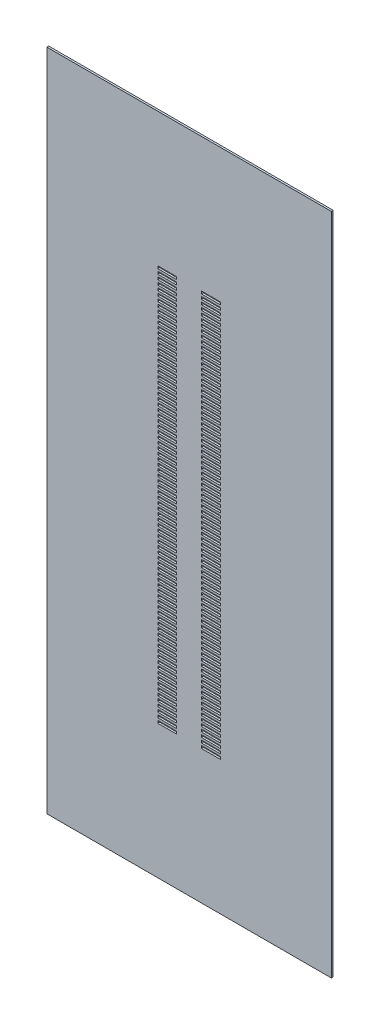
SolidWorks part; units mm, degrees
ref_plane "Front Plane" through (0, 0, 0) normal (0, 0, 1) x (1, 0, 0)
ref_plane "Top Plane" through (0, 0, 0) normal (0, 1, 0) x (1, 0, 0)
ref_plane "Right Plane" through (0, 0, 0) normal (1, 0, 0) x (0, 0, -1)
sketch "Sketch1" plane through (0, 0, 0) normal (0, 0, 1) x (1, 0, 0)
  line L1340 (-1.3, -0.27) -> (-1.3, 0)
  line L1341 (-1.3, 0) -> (-3.3, 0)
  line L1342 (-3.3, 0) -> (-3.3, -0.27)
  line L1343 (-3.3, -0.27) -> (-1.3, -0.27)
  line L2016 (-1.3, 0) -> (1.3, 0) construction
  line L2017 (0, 0) -> (0, -41.77) construction
  line L2018 (1.3, -0.27) -> (1.3, 0)
  line L2019 (3.3, -0.27) -> (1.3, -0.27)
  line L2020 (3.3, 0) -> (3.3, -0.27)
  line L2021 (1.3, 0) -> (3.3, 0)
  line L2022 (1.3, -0.5) -> (3.3, -0.5)
  line L2023 (3.3, -0.5) -> (3.3, -0.77)
  line L2024 (3.3, -0.77) -> (1.3, -0.77)
  line L2025 (1.3, -0.77) -> (1.3, -0.5)
  line L2026 (-1.3, -0.5) -> (-3.3, -0.5)
  line L2027 (-3.3, -0.5) -> (-3.3, -0.77)
  line L2028 (-3.3, -0.77) -> (-1.3, -0.77)
  line L2029 (-1.3, -0.77) -> (-1.3, -0.5)
  line L2030 (1.3, -1) -> (3.3, -1)
  line L2031 (3.3, -1) -> (3.3, -1.27)
  line L2032 (3.3, -1.27) -> (1.3, -1.27)
  line L2033 (1.3, -1.27) -> (1.3, -1)
  line L2034 (-1.3, -1) -> (-3.3, -1)
  line L2035 (-3.3, -1) -> (-3.3, -1.27)
  line L2036 (-3.3, -1.27) -> (-1.3, -1.27)
  line L2037 (-1.3, -1.27) -> (-1.3, -1)
  line L2038 (1.3, -1.5) -> (3.3, -1.5)
  line L2039 (3.3, -1.5) -> (3.3, -1.77)
  line L2040 (3.3, -1.77) -> (1.3, -1.77)
  line L2041 (1.3, -1.77) -> (1.3, -1.5)
  line L2042 (-1.3, -1.5) -> (-3.3, -1.5)
  line L2043 (-3.3, -1.5) -> (-3.3, -1.77)
  line L2044 (-3.3, -1.77) -> (-1.3, -1.77)
  line L2045 (-1.3, -1.77) -> (-1.3, -1.5)
  line L2046 (1.3, -2) -> (3.3, -2)
  line L2047 (3.3, -2) -> (3.3, -2.27)
  line L2048 (3.3, -2.27) -> (1.3, -2.27)
  line L2049 (1.3, -2.27) -> (1.3, -2)
  line L2050 (-1.3, -2) -> (-3.3, -2)
  line L2051 (-3.3, -2) -> (-3.3, -2.27)
  line L2052 (-3.3, -2.27) -> (-1.3, -2.27)
  line L2053 (-1.3, -2.27) -> (-1.3, -2)
  line L2054 (1.3, -2.5) -> (3.3, -2.5)
  line L2055 (3.3, -2.5) -> (3.3, -2.77)
  line L2056 (3.3, -2.77) -> (1.3, -2.77)
  line L2057 (1.3, -2.77) -> (1.3, -2.5)
  line L2058 (-1.3, -2.5) -> (-3.3, -2.5)
  line L2059 (-3.3, -2.5) -> (-3.3, -2.77)
  line L2060 (-3.3, -2.77) -> (-1.3, -2.77)
  line L2061 (-1.3, -2.77) -> (-1.3, -2.5)
  line L2062 (1.3, -3) -> (3.3, -3)
  line L2063 (3.3, -3) -> (3.3, -3.27)
  line L2064 (3.3, -3.27) -> (1.3, -3.27)
  line L2065 (1.3, -3.27) -> (1.3, -3)
  line L2066 (-1.3, -3) -> (-3.3, -3)
  line L2067 (-3.3, -3) -> (-3.3, -3.27)
  line L2068 (-3.3, -3.27) -> (-1.3, -3.27)
  line L2069 (-1.3, -3.27) -> (-1.3, -3)
  line L2070 (1.3, -3.5) -> (3.3, -3.5)
  line L2071 (3.3, -3.5) -> (3.3, -3.77)
  line L2072 (3.3, -3.77) -> (1.3, -3.77)
  line L2073 (1.3, -3.77) -> (1.3, -3.5)
  line L2074 (-1.3, -3.5) -> (-3.3, -3.5)
  line L2075 (-3.3, -3.5) -> (-3.3, -3.77)
  line L2076 (-3.3, -3.77) -> (-1.3, -3.77)
  line L2077 (-1.3, -3.77) -> (-1.3, -3.5)
  line L2078 (1.3, -4) -> (3.3, -4)
  line L2079 (3.3, -4) -> (3.3, -4.27)
  line L2080 (3.3, -4.27) -> (1.3, -4.27)
  line L2081 (1.3, -4.27) -> (1.3, -4)
  line L2082 (-1.3, -4) -> (-3.3, -4)
  line L2083 (-3.3, -4) -> (-3.3, -4.27)
  line L2084 (-3.3, -4.27) -> (-1.3, -4.27)
  line L2085 (-1.3, -4.27) -> (-1.3, -4)
  line L2086 (1.3, -4.5) -> (3.3, -4.5)
  line L2087 (3.3, -4.5) -> (3.3, -4.77)
  line L2088 (3.3, -4.77) -> (1.3, -4.77)
  line L2089 (1.3, -4.77) -> (1.3, -4.5)
  line L2090 (-1.3, -4.5) -> (-3.3, -4.5)
  line L2091 (-3.3, -4.5) -> (-3.3, -4.77)
  line L2092 (-3.3, -4.77) -> (-1.3, -4.77)
  line L2093 (-1.3, -4.77) -> (-1.3, -4.5)
  line L2094 (1.3, -5) -> (3.3, -5)
  line L2095 (3.3, -5) -> (3.3, -5.27)
  line L2096 (3.3, -5.27) -> (1.3, -5.27)
  line L2097 (1.3, -5.27) -> (1.3, -5)
  line L2098 (-1.3, -5) -> (-3.3, -5)
  line L2099 (-3.3, -5) -> (-3.3, -5.27)
  line L2100 (-3.3, -5.27) -> (-1.3, -5.27)
  line L2101 (-1.3, -5.27) -> (-1.3, -5)
  line L2102 (1.3, -5.5) -> (3.3, -5.5)
  line L2103 (3.3, -5.5) -> (3.3, -5.77)
  line L2104 (3.3, -5.77) -> (1.3, -5.77)
  line L2105 (1.3, -5.77) -> (1.3, -5.5)
  line L2106 (-1.3, -5.5) -> (-3.3, -5.5)
  line L2107 (-3.3, -5.5) -> (-3.3, -5.77)
  line L2108 (-3.3, -5.77) -> (-1.3, -5.77)
  line L2109 (-1.3, -5.77) -> (-1.3, -5.5)
  line L2110 (1.3, -6) -> (3.3, -6)
  line L2111 (3.3, -6) -> (3.3, -6.27)
  line L2112 (3.3, -6.27) -> (1.3, -6.27)
  line L2113 (1.3, -6.27) -> (1.3, -6)
  line L2114 (-1.3, -6) -> (-3.3, -6)
  line L2115 (-3.3, -6) -> (-3.3, -6.27)
  line L2116 (-3.3, -6.27) -> (-1.3, -6.27)
  line L2117 (-1.3, -6.27) -> (-1.3, -6)
  line L2118 (1.3, -6.5) -> (3.3, -6.5)
  line L2119 (3.3, -6.5) -> (3.3, -6.77)
  line L2120 (3.3, -6.77) -> (1.3, -6.77)
  line L2121 (1.3, -6.77) -> (1.3, -6.5)
  line L2122 (-1.3, -6.5) -> (-3.3, -6.5)
  line L2123 (-3.3, -6.5) -> (-3.3, -6.77)
  line L2124 (-3.3, -6.77) -> (-1.3, -6.77)
  line L2125 (-1.3, -6.77) -> (-1.3, -6.5)
  line L2126 (1.3, -7) -> (3.3, -7)
  line L2127 (3.3, -7) -> (3.3, -7.27)
  line L2128 (3.3, -7.27) -> (1.3, -7.27)
  line L2129 (1.3, -7.27) -> (1.3, -7)
  line L2130 (-1.3, -7) -> (-3.3, -7)
  line L2131 (-3.3, -7) -> (-3.3, -7.27)
  line L2132 (-3.3, -7.27) -> (-1.3, -7.27)
  line L2133 (-1.3, -7.27) -> (-1.3, -7)
  line L2134 (1.3, -7.5) -> (3.3, -7.5)
  line L2135 (3.3, -7.5) -> (3.3, -7.77)
  line L2136 (3.3, -7.77) -> (1.3, -7.77)
  line L2137 (1.3, -7.77) -> (1.3, -7.5)
  line L2138 (-1.3, -7.5) -> (-3.3, -7.5)
  line L2139 (-3.3, -7.5) -> (-3.3, -7.77)
  line L2140 (-3.3, -7.77) -> (-1.3, -7.77)
  line L2141 (-1.3, -7.77) -> (-1.3, -7.5)
  line L2142 (1.3, -8) -> (3.3, -8)
  line L2143 (3.3, -8) -> (3.3, -8.27)
  line L2144 (3.3, -8.27) -> (1.3, -8.27)
  line L2145 (1.3, -8.27) -> (1.3, -8)
  line L2146 (-1.3, -8) -> (-3.3, -8)
  line L2147 (-3.3, -8) -> (-3.3, -8.27)
  line L2148 (-3.3, -8.27) -> (-1.3, -8.27)
  line L2149 (-1.3, -8.27) -> (-1.3, -8)
  line L2150 (1.3, -8.5) -> (3.3, -8.5)
  line L2151 (3.3, -8.5) -> (3.3, -8.77)
  line L2152 (3.3, -8.77) -> (1.3, -8.77)
  line L2153 (1.3, -8.77) -> (1.3, -8.5)
  line L2154 (-1.3, -8.5) -> (-3.3, -8.5)
  line L2155 (-3.3, -8.5) -> (-3.3, -8.77)
  line L2156 (-3.3, -8.77) -> (-1.3, -8.77)
  line L2157 (-1.3, -8.77) -> (-1.3, -8.5)
  line L2158 (1.3, -9) -> (3.3, -9)
  line L2159 (3.3, -9) -> (3.3, -9.27)
  line L2160 (3.3, -9.27) -> (1.3, -9.27)
  line L2161 (1.3, -9.27) -> (1.3, -9)
  line L2162 (-1.3, -9) -> (-3.3, -9)
  line L2163 (-3.3, -9) -> (-3.3, -9.27)
  line L2164 (-3.3, -9.27) -> (-1.3, -9.27)
  line L2165 (-1.3, -9.27) -> (-1.3, -9)
  line L2166 (1.3, -9.5) -> (3.3, -9.5)
  line L2167 (3.3, -9.5) -> (3.3, -9.77)
  line L2168 (3.3, -9.77) -> (1.3, -9.77)
  line L2169 (1.3, -9.77) -> (1.3, -9.5)
  line L2170 (-1.3, -9.5) -> (-3.3, -9.5)
  line L2171 (-3.3, -9.5) -> (-3.3, -9.77)
  line L2172 (-3.3, -9.77) -> (-1.3, -9.77)
  line L2173 (-1.3, -9.77) -> (-1.3, -9.5)
  line L2174 (1.3, -10) -> (3.3, -10)
  line L2175 (3.3, -10) -> (3.3, -10.27)
  line L2176 (3.3, -10.27) -> (1.3, -10.27)
  line L2177 (1.3, -10.27) -> (1.3, -10)
  line L2178 (-1.3, -10) -> (-3.3, -10)
  line L2179 (-3.3, -10) -> (-3.3, -10.27)
  line L2180 (-3.3, -10.27) -> (-1.3, -10.27)
  line L2181 (-1.3, -10.27) -> (-1.3, -10)
  line L2182 (1.3, -10.5) -> (3.3, -10.5)
  line L2183 (3.3, -10.5) -> (3.3, -10.77)
  line L2184 (3.3, -10.77) -> (1.3, -10.77)
  line L2185 (1.3, -10.77) -> (1.3, -10.5)
  line L2186 (-1.3, -10.5) -> (-3.3, -10.5)
  line L2187 (-3.3, -10.5) -> (-3.3, -10.77)
  line L2188 (-3.3, -10.77) -> (-1.3, -10.77)
  line L2189 (-1.3, -10.77) -> (-1.3, -10.5)
  line L2190 (1.3, -11) -> (3.3, -11)
  line L2191 (3.3, -11) -> (3.3, -11.27)
  line L2192 (3.3, -11.27) -> (1.3, -11.27)
  line L2193 (1.3, -11.27) -> (1.3, -11)
  line L2194 (-1.3, -11) -> (-3.3, -11)
  line L2195 (-3.3, -11) -> (-3.3, -11.27)
  line L2196 (-3.3, -11.27) -> (-1.3, -11.27)
  line L2197 (-1.3, -11.27) -> (-1.3, -11)
  line L2198 (1.3, -11.5) -> (3.3, -11.5)
  line L2199 (3.3, -11.5) -> (3.3, -11.77)
  line L2200 (3.3, -11.77) -> (1.3, -11.77)
  line L2201 (1.3, -11.77) -> (1.3, -11.5)
  line L2202 (-1.3, -11.5) -> (-3.3, -11.5)
  line L2203 (-3.3, -11.5) -> (-3.3, -11.77)
  line L2204 (-3.3, -11.77) -> (-1.3, -11.77)
  line L2205 (-1.3, -11.77) -> (-1.3, -11.5)
  line L2206 (1.3, -12) -> (3.3, -12)
  line L2207 (3.3, -12) -> (3.3, -12.27)
  line L2208 (3.3, -12.27) -> (1.3, -12.27)
  line L2209 (1.3, -12.27) -> (1.3, -12)
  line L2210 (-1.3, -12) -> (-3.3, -12)
  line L2211 (-3.3, -12) -> (-3.3, -12.27)
  line L2212 (-3.3, -12.27) -> (-1.3, -12.27)
  line L2213 (-1.3, -12.27) -> (-1.3, -12)
  line L2214 (1.3, -12.5) -> (3.3, -12.5)
  line L2215 (3.3, -12.5) -> (3.3, -12.77)
  line L2216 (3.3, -12.77) -> (1.3, -12.77)
  line L2217 (1.3, -12.77) -> (1.3, -12.5)
  line L2218 (-1.3, -12.5) -> (-3.3, -12.5)
  line L2219 (-3.3, -12.5) -> (-3.3, -12.77)
  line L2220 (-3.3, -12.77) -> (-1.3, -12.77)
  line L2221 (-1.3, -12.77) -> (-1.3, -12.5)
  line L2222 (1.3, -13) -> (3.3, -13)
  line L2223 (3.3, -13) -> (3.3, -13.27)
  line L2224 (3.3, -13.27) -> (1.3, -13.27)
  line L2225 (1.3, -13.27) -> (1.3, -13)
  line L2226 (-1.3, -13) -> (-3.3, -13)
  line L2227 (-3.3, -13) -> (-3.3, -13.27)
  line L2228 (-3.3, -13.27) -> (-1.3, -13.27)
  line L2229 (-1.3, -13.27) -> (-1.3, -13)
  line L2230 (1.3, -13.5) -> (3.3, -13.5)
  line L2231 (3.3, -13.5) -> (3.3, -13.77)
  line L2232 (3.3, -13.77) -> (1.3, -13.77)
  line L2233 (1.3, -13.77) -> (1.3, -13.5)
  line L2234 (-1.3, -13.5) -> (-3.3, -13.5)
  line L2235 (-3.3, -13.5) -> (-3.3, -13.77)
  line L2236 (-3.3, -13.77) -> (-1.3, -13.77)
  line L2237 (-1.3, -13.77) -> (-1.3, -13.5)
  line L2238 (1.3, -14) -> (3.3, -14)
  line L2239 (3.3, -14) -> (3.3, -14.27)
  line L2240 (3.3, -14.27) -> (1.3, -14.27)
  line L2241 (1.3, -14.27) -> (1.3, -14)
  line L2242 (-1.3, -14) -> (-3.3, -14)
  line L2243 (-3.3, -14) -> (-3.3, -14.27)
  line L2244 (-3.3, -14.27) -> (-1.3, -14.27)
  line L2245 (-1.3, -14.27) -> (-1.3, -14)
  line L2246 (1.3, -14.5) -> (3.3, -14.5)
  line L2247 (3.3, -14.5) -> (3.3, -14.77)
  line L2248 (3.3, -14.77) -> (1.3, -14.77)
  line L2249 (1.3, -14.77) -> (1.3, -14.5)
  line L2250 (-1.3, -14.5) -> (-3.3, -14.5)
  line L2251 (-3.3, -14.5) -> (-3.3, -14.77)
  line L2252 (-3.3, -14.77) -> (-1.3, -14.77)
  line L2253 (-1.3, -14.77) -> (-1.3, -14.5)
  line L2254 (1.3, -15) -> (3.3, -15)
  line L2255 (3.3, -15) -> (3.3, -15.27)
  line L2256 (3.3, -15.27) -> (1.3, -15.27)
  line L2257 (1.3, -15.27) -> (1.3, -15)
  line L2258 (-1.3, -15) -> (-3.3, -15)
  line L2259 (-3.3, -15) -> (-3.3, -15.27)
  line L2260 (-3.3, -15.27) -> (-1.3, -15.27)
  line L2261 (-1.3, -15.27) -> (-1.3, -15)
  line L2262 (1.3, -15.5) -> (3.3, -15.5)
  line L2263 (3.3, -15.5) -> (3.3, -15.77)
  line L2264 (3.3, -15.77) -> (1.3, -15.77)
  line L2265 (1.3, -15.77) -> (1.3, -15.5)
  line L2266 (-1.3, -15.5) -> (-3.3, -15.5)
  line L2267 (-3.3, -15.5) -> (-3.3, -15.77)
  line L2268 (-3.3, -15.77) -> (-1.3, -15.77)
  line L2269 (-1.3, -15.77) -> (-1.3, -15.5)
  line L2270 (1.3, -16) -> (3.3, -16)
  line L2271 (3.3, -16) -> (3.3, -16.27)
  line L2272 (3.3, -16.27) -> (1.3, -16.27)
  line L2273 (1.3, -16.27) -> (1.3, -16)
  line L2274 (-1.3, -16) -> (-3.3, -16)
  line L2275 (-3.3, -16) -> (-3.3, -16.27)
  line L2276 (-3.3, -16.27) -> (-1.3, -16.27)
  line L2277 (-1.3, -16.27) -> (-1.3, -16)
  line L2278 (1.3, -16.5) -> (3.3, -16.5)
  line L2279 (3.3, -16.5) -> (3.3, -16.77)
  line L2280 (3.3, -16.77) -> (1.3, -16.77)
  line L2281 (1.3, -16.77) -> (1.3, -16.5)
  line L2282 (-1.3, -16.5) -> (-3.3, -16.5)
  line L2283 (-3.3, -16.5) -> (-3.3, -16.77)
  line L2284 (-3.3, -16.77) -> (-1.3, -16.77)
  line L2285 (-1.3, -16.77) -> (-1.3, -16.5)
  line L2286 (1.3, -17) -> (3.3, -17)
  line L2287 (3.3, -17) -> (3.3, -17.27)
  line L2288 (3.3, -17.27) -> (1.3, -17.27)
  line L2289 (1.3, -17.27) -> (1.3, -17)
  line L2290 (-1.3, -17) -> (-3.3, -17)
  line L2291 (-3.3, -17) -> (-3.3, -17.27)
  line L2292 (-3.3, -17.27) -> (-1.3, -17.27)
  line L2293 (-1.3, -17.27) -> (-1.3, -17)
  line L2294 (1.3, -17.5) -> (3.3, -17.5)
  line L2295 (3.3, -17.5) -> (3.3, -17.77)
  line L2296 (3.3, -17.77) -> (1.3, -17.77)
  line L2297 (1.3, -17.77) -> (1.3, -17.5)
  line L2298 (-1.3, -17.5) -> (-3.3, -17.5)
  line L2299 (-3.3, -17.5) -> (-3.3, -17.77)
  line L2300 (-3.3, -17.77) -> (-1.3, -17.77)
  line L2301 (-1.3, -17.77) -> (-1.3, -17.5)
  line L2302 (1.3, -18) -> (3.3, -18)
  line L2303 (3.3, -18) -> (3.3, -18.27)
  line L2304 (3.3, -18.27) -> (1.3, -18.27)
  line L2305 (1.3, -18.27) -> (1.3, -18)
  line L2306 (-1.3, -18) -> (-3.3, -18)
  line L2307 (-3.3, -18) -> (-3.3, -18.27)
  line L2308 (-3.3, -18.27) -> (-1.3, -18.27)
  line L2309 (-1.3, -18.27) -> (-1.3, -18)
  line L2310 (1.3, -18.5) -> (3.3, -18.5)
  line L2311 (3.3, -18.5) -> (3.3, -18.77)
  line L2312 (3.3, -18.77) -> (1.3, -18.77)
  line L2313 (1.3, -18.77) -> (1.3, -18.5)
  line L2314 (-1.3, -18.5) -> (-3.3, -18.5)
  line L2315 (-3.3, -18.5) -> (-3.3, -18.77)
  line L2316 (-3.3, -18.77) -> (-1.3, -18.77)
  line L2317 (-1.3, -18.77) -> (-1.3, -18.5)
  line L2318 (1.3, -19) -> (3.3, -19)
  line L2319 (3.3, -19) -> (3.3, -19.27)
  line L2320 (3.3, -19.27) -> (1.3, -19.27)
  line L2321 (1.3, -19.27) -> (1.3, -19)
  line L2322 (-1.3, -19) -> (-3.3, -19)
  line L2323 (-3.3, -19) -> (-3.3, -19.27)
  line L2324 (-3.3, -19.27) -> (-1.3, -19.27)
  line L2325 (-1.3, -19.27) -> (-1.3, -19)
  line L2326 (1.3, -19.5) -> (3.3, -19.5)
  line L2327 (3.3, -19.5) -> (3.3, -19.77)
  line L2328 (3.3, -19.77) -> (1.3, -19.77)
  line L2329 (1.3, -19.77) -> (1.3, -19.5)
  line L2330 (-1.3, -19.5) -> (-3.3, -19.5)
  line L2331 (-3.3, -19.5) -> (-3.3, -19.77)
  line L2332 (-3.3, -19.77) -> (-1.3, -19.77)
  line L2333 (-1.3, -19.77) -> (-1.3, -19.5)
  line L2334 (1.3, -20) -> (3.3, -20)
  line L2335 (3.3, -20) -> (3.3, -20.27)
  line L2336 (3.3, -20.27) -> (1.3, -20.27)
  line L2337 (1.3, -20.27) -> (1.3, -20)
  line L2338 (-1.3, -20) -> (-3.3, -20)
  line L2339 (-3.3, -20) -> (-3.3, -20.27)
  line L2340 (-3.3, -20.27) -> (-1.3, -20.27)
  line L2341 (-1.3, -20.27) -> (-1.3, -20)
  line L2342 (1.3, -20.5) -> (3.3, -20.5)
  line L2343 (3.3, -20.5) -> (3.3, -20.77)
  line L2344 (3.3, -20.77) -> (1.3, -20.77)
  line L2345 (1.3, -20.77) -> (1.3, -20.5)
  line L2346 (-1.3, -20.5) -> (-3.3, -20.5)
  line L2347 (-3.3, -20.5) -> (-3.3, -20.77)
  line L2348 (-3.3, -20.77) -> (-1.3, -20.77)
  line L2349 (-1.3, -20.77) -> (-1.3, -20.5)
  line L2350 (1.3, -21) -> (3.3, -21)
  line L2351 (3.3, -21) -> (3.3, -21.27)
  line L2352 (3.3, -21.27) -> (1.3, -21.27)
  line L2353 (1.3, -21.27) -> (1.3, -21)
  line L2354 (-1.3, -21) -> (-3.3, -21)
  line L2355 (-3.3, -21) -> (-3.3, -21.27)
  line L2356 (-3.3, -21.27) -> (-1.3, -21.27)
  line L2357 (-1.3, -21.27) -> (-1.3, -21)
  line L2358 (1.3, -21.5) -> (3.3, -21.5)
  line L2359 (3.3, -21.5) -> (3.3, -21.77)
  line L2360 (3.3, -21.77) -> (1.3, -21.77)
  line L2361 (1.3, -21.77) -> (1.3, -21.5)
  line L2362 (-1.3, -21.5) -> (-3.3, -21.5)
  line L2363 (-3.3, -21.5) -> (-3.3, -21.77)
  line L2364 (-3.3, -21.77) -> (-1.3, -21.77)
  line L2365 (-1.3, -21.77) -> (-1.3, -21.5)
  line L2366 (1.3, -22) -> (3.3, -22)
  line L2367 (3.3, -22) -> (3.3, -22.27)
  line L2368 (3.3, -22.27) -> (1.3, -22.27)
  line L2369 (1.3, -22.27) -> (1.3, -22)
  line L2370 (-1.3, -22) -> (-3.3, -22)
  line L2371 (-3.3, -22) -> (-3.3, -22.27)
  line L2372 (-3.3, -22.27) -> (-1.3, -22.27)
  line L2373 (-1.3, -22.27) -> (-1.3, -22)
  line L2374 (1.3, -22.5) -> (3.3, -22.5)
  line L2375 (3.3, -22.5) -> (3.3, -22.77)
  line L2376 (3.3, -22.77) -> (1.3, -22.77)
  line L2377 (1.3, -22.77) -> (1.3, -22.5)
  line L2378 (-1.3, -22.5) -> (-3.3, -22.5)
  line L2379 (-3.3, -22.5) -> (-3.3, -22.77)
  line L2380 (-3.3, -22.77) -> (-1.3, -22.77)
  line L2381 (-1.3, -22.77) -> (-1.3, -22.5)
  line L2382 (1.3, -23) -> (3.3, -23)
  line L2383 (3.3, -23) -> (3.3, -23.27)
  line L2384 (3.3, -23.27) -> (1.3, -23.27)
  line L2385 (1.3, -23.27) -> (1.3, -23)
  line L2386 (-1.3, -23) -> (-3.3, -23)
  line L2387 (-3.3, -23) -> (-3.3, -23.27)
  line L2388 (-3.3, -23.27) -> (-1.3, -23.27)
  line L2389 (-1.3, -23.27) -> (-1.3, -23)
  line L2390 (1.3, -23.5) -> (3.3, -23.5)
  line L2391 (3.3, -23.5) -> (3.3, -23.77)
  line L2392 (3.3, -23.77) -> (1.3, -23.77)
  line L2393 (1.3, -23.77) -> (1.3, -23.5)
  line L2394 (-1.3, -23.5) -> (-3.3, -23.5)
  line L2395 (-3.3, -23.5) -> (-3.3, -23.77)
  line L2396 (-3.3, -23.77) -> (-1.3, -23.77)
  line L2397 (-1.3, -23.77) -> (-1.3, -23.5)
  line L2398 (1.3, -24) -> (3.3, -24)
  line L2399 (3.3, -24) -> (3.3, -24.27)
  line L2400 (3.3, -24.27) -> (1.3, -24.27)
  line L2401 (1.3, -24.27) -> (1.3, -24)
  line L2402 (-1.3, -24) -> (-3.3, -24)
  line L2403 (-3.3, -24) -> (-3.3, -24.27)
  line L2404 (-3.3, -24.27) -> (-1.3, -24.27)
  line L2405 (-1.3, -24.27) -> (-1.3, -24)
  line L2406 (1.3, -24.5) -> (3.3, -24.5)
  line L2407 (3.3, -24.5) -> (3.3, -24.77)
  line L2408 (3.3, -24.77) -> (1.3, -24.77)
  line L2409 (1.3, -24.77) -> (1.3, -24.5)
  line L2410 (-1.3, -24.5) -> (-3.3, -24.5)
  line L2411 (-3.3, -24.5) -> (-3.3, -24.77)
  line L2412 (-3.3, -24.77) -> (-1.3, -24.77)
  line L2413 (-1.3, -24.77) -> (-1.3, -24.5)
  line L2414 (1.3, -25) -> (3.3, -25)
  line L2415 (3.3, -25) -> (3.3, -25.27)
  line L2416 (3.3, -25.27) -> (1.3, -25.27)
  line L2417 (1.3, -25.27) -> (1.3, -25)
  line L2418 (-1.3, -25) -> (-3.3, -25)
  line L2419 (-3.3, -25) -> (-3.3, -25.27)
  line L2420 (-3.3, -25.27) -> (-1.3, -25.27)
  line L2421 (-1.3, -25.27) -> (-1.3, -25)
  line L2422 (1.3, -25.5) -> (3.3, -25.5)
  line L2423 (3.3, -25.5) -> (3.3, -25.77)
  line L2424 (3.3, -25.77) -> (1.3, -25.77)
  line L2425 (1.3, -25.77) -> (1.3, -25.5)
  line L2426 (-1.3, -25.5) -> (-3.3, -25.5)
  line L2427 (-3.3, -25.5) -> (-3.3, -25.77)
  line L2428 (-3.3, -25.77) -> (-1.3, -25.77)
  line L2429 (-1.3, -25.77) -> (-1.3, -25.5)
  line L2430 (1.3, -26) -> (3.3, -26)
  line L2431 (3.3, -26) -> (3.3, -26.27)
  line L2432 (3.3, -26.27) -> (1.3, -26.27)
  line L2433 (1.3, -26.27) -> (1.3, -26)
  line L2434 (-1.3, -26) -> (-3.3, -26)
  line L2435 (-3.3, -26) -> (-3.3, -26.27)
  line L2436 (-3.3, -26.27) -> (-1.3, -26.27)
  line L2437 (-1.3, -26.27) -> (-1.3, -26)
  line L2438 (1.3, -26.5) -> (3.3, -26.5)
  line L2439 (3.3, -26.5) -> (3.3, -26.77)
  line L2440 (3.3, -26.77) -> (1.3, -26.77)
  line L2441 (1.3, -26.77) -> (1.3, -26.5)
  line L2442 (-1.3, -26.5) -> (-3.3, -26.5)
  line L2443 (-3.3, -26.5) -> (-3.3, -26.77)
  line L2444 (-3.3, -26.77) -> (-1.3, -26.77)
  line L2445 (-1.3, -26.77) -> (-1.3, -26.5)
  line L2446 (1.3, -27) -> (3.3, -27)
  line L2447 (3.3, -27) -> (3.3, -27.27)
  line L2448 (3.3, -27.27) -> (1.3, -27.27)
  line L2449 (1.3, -27.27) -> (1.3, -27)
  line L2450 (-1.3, -27) -> (-3.3, -27)
  line L2451 (-3.3, -27) -> (-3.3, -27.27)
  line L2452 (-3.3, -27.27) -> (-1.3, -27.27)
  line L2453 (-1.3, -27.27) -> (-1.3, -27)
  line L2454 (1.3, -27.5) -> (3.3, -27.5)
  line L2455 (3.3, -27.5) -> (3.3, -27.77)
  line L2456 (3.3, -27.77) -> (1.3, -27.77)
  line L2457 (1.3, -27.77) -> (1.3, -27.5)
  line L2458 (-1.3, -27.5) -> (-3.3, -27.5)
  line L2459 (-3.3, -27.5) -> (-3.3, -27.77)
  line L2460 (-3.3, -27.77) -> (-1.3, -27.77)
  line L2461 (-1.3, -27.77) -> (-1.3, -27.5)
  line L2462 (1.3, -28) -> (3.3, -28)
  line L2463 (3.3, -28) -> (3.3, -28.27)
  line L2464 (3.3, -28.27) -> (1.3, -28.27)
  line L2465 (1.3, -28.27) -> (1.3, -28)
  line L2466 (-1.3, -28) -> (-3.3, -28)
  line L2467 (-3.3, -28) -> (-3.3, -28.27)
  line L2468 (-3.3, -28.27) -> (-1.3, -28.27)
  line L2469 (-1.3, -28.27) -> (-1.3, -28)
  line L2470 (1.3, -28.5) -> (3.3, -28.5)
  line L2471 (3.3, -28.5) -> (3.3, -28.77)
  line L2472 (3.3, -28.77) -> (1.3, -28.77)
  line L2473 (1.3, -28.77) -> (1.3, -28.5)
  line L2474 (-1.3, -28.5) -> (-3.3, -28.5)
  line L2475 (-3.3, -28.5) -> (-3.3, -28.77)
  line L2476 (-3.3, -28.77) -> (-1.3, -28.77)
  line L2477 (-1.3, -28.77) -> (-1.3, -28.5)
  line L2478 (1.3, -29) -> (3.3, -29)
  line L2479 (3.3, -29) -> (3.3, -29.27)
  line L2480 (3.3, -29.27) -> (1.3, -29.27)
  line L2481 (1.3, -29.27) -> (1.3, -29)
  line L2482 (-1.3, -29) -> (-3.3, -29)
  line L2483 (-3.3, -29) -> (-3.3, -29.27)
  line L2484 (-3.3, -29.27) -> (-1.3, -29.27)
  line L2485 (-1.3, -29.27) -> (-1.3, -29)
  line L2486 (1.3, -29.5) -> (3.3, -29.5)
  line L2487 (3.3, -29.5) -> (3.3, -29.77)
  line L2488 (3.3, -29.77) -> (1.3, -29.77)
  line L2489 (1.3, -29.77) -> (1.3, -29.5)
  line L2490 (-1.3, -29.5) -> (-3.3, -29.5)
  line L2491 (-3.3, -29.5) -> (-3.3, -29.77)
  line L2492 (-3.3, -29.77) -> (-1.3, -29.77)
  line L2493 (-1.3, -29.77) -> (-1.3, -29.5)
  line L2494 (1.3, -30) -> (3.3, -30)
  line L2495 (3.3, -30) -> (3.3, -30.27)
  line L2496 (3.3, -30.27) -> (1.3, -30.27)
  line L2497 (1.3, -30.27) -> (1.3, -30)
  line L2498 (-1.3, -30) -> (-3.3, -30)
  line L2499 (-3.3, -30) -> (-3.3, -30.27)
  line L2500 (-3.3, -30.27) -> (-1.3, -30.27)
  line L2501 (-1.3, -30.27) -> (-1.3, -30)
  line L2502 (1.3, -30.5) -> (3.3, -30.5)
  line L2503 (3.3, -30.5) -> (3.3, -30.77)
  line L2504 (3.3, -30.77) -> (1.3, -30.77)
  line L2505 (1.3, -30.77) -> (1.3, -30.5)
  line L2506 (-1.3, -30.5) -> (-3.3, -30.5)
  line L2507 (-3.3, -30.5) -> (-3.3, -30.77)
  line L2508 (-3.3, -30.77) -> (-1.3, -30.77)
  line L2509 (-1.3, -30.77) -> (-1.3, -30.5)
  line L2510 (1.3, -31) -> (3.3, -31)
  line L2511 (3.3, -31) -> (3.3, -31.27)
  line L2512 (3.3, -31.27) -> (1.3, -31.27)
  line L2513 (1.3, -31.27) -> (1.3, -31)
  line L2514 (-1.3, -31) -> (-3.3, -31)
  line L2515 (-3.3, -31) -> (-3.3, -31.27)
  line L2516 (-3.3, -31.27) -> (-1.3, -31.27)
  line L2517 (-1.3, -31.27) -> (-1.3, -31)
  line L2518 (1.3, -31.5) -> (3.3, -31.5)
  line L2519 (3.3, -31.5) -> (3.3, -31.77)
  line L2520 (3.3, -31.77) -> (1.3, -31.77)
  line L2521 (1.3, -31.77) -> (1.3, -31.5)
  line L2522 (-1.3, -31.5) -> (-3.3, -31.5)
  line L2523 (-3.3, -31.5) -> (-3.3, -31.77)
  line L2524 (-3.3, -31.77) -> (-1.3, -31.77)
  line L2525 (-1.3, -31.77) -> (-1.3, -31.5)
  line L2526 (1.3, -32) -> (3.3, -32)
  line L2527 (3.3, -32) -> (3.3, -32.27)
  line L2528 (3.3, -32.27) -> (1.3, -32.27)
  line L2529 (1.3, -32.27) -> (1.3, -32)
  line L2530 (-1.3, -32) -> (-3.3, -32)
  line L2531 (-3.3, -32) -> (-3.3, -32.27)
  line L2532 (-3.3, -32.27) -> (-1.3, -32.27)
  line L2533 (-1.3, -32.27) -> (-1.3, -32)
  line L2534 (1.3, -32.5) -> (3.3, -32.5)
  line L2535 (3.3, -32.5) -> (3.3, -32.77)
  line L2536 (3.3, -32.77) -> (1.3, -32.77)
  line L2537 (1.3, -32.77) -> (1.3, -32.5)
  line L2538 (-1.3, -32.5) -> (-3.3, -32.5)
  line L2539 (-3.3, -32.5) -> (-3.3, -32.77)
  line L2540 (-3.3, -32.77) -> (-1.3, -32.77)
  line L2541 (-1.3, -32.77) -> (-1.3, -32.5)
  line L2542 (1.3, -33) -> (3.3, -33)
  line L2543 (3.3, -33) -> (3.3, -33.27)
  line L2544 (3.3, -33.27) -> (1.3, -33.27)
  line L2545 (1.3, -33.27) -> (1.3, -33)
  line L2546 (-1.3, -33) -> (-3.3, -33)
  line L2547 (-3.3, -33) -> (-3.3, -33.27)
  line L2548 (-3.3, -33.27) -> (-1.3, -33.27)
  line L2549 (-1.3, -33.27) -> (-1.3, -33)
  line L2550 (1.3, -33.5) -> (3.3, -33.5)
  line L2551 (3.3, -33.5) -> (3.3, -33.77)
  line L2552 (3.3, -33.77) -> (1.3, -33.77)
  line L2553 (1.3, -33.77) -> (1.3, -33.5)
  line L2554 (-1.3, -33.5) -> (-3.3, -33.5)
  line L2555 (-3.3, -33.5) -> (-3.3, -33.77)
  line L2556 (-3.3, -33.77) -> (-1.3, -33.77)
  line L2557 (-1.3, -33.77) -> (-1.3, -33.5)
  line L2558 (1.3, -34) -> (3.3, -34)
  line L2559 (3.3, -34) -> (3.3, -34.27)
  line L2560 (3.3, -34.27) -> (1.3, -34.27)
  line L2561 (1.3, -34.27) -> (1.3, -34)
  line L2562 (-1.3, -34) -> (-3.3, -34)
  line L2563 (-3.3, -34) -> (-3.3, -34.27)
  line L2564 (-3.3, -34.27) -> (-1.3, -34.27)
  line L2565 (-1.3, -34.27) -> (-1.3, -34)
  line L2566 (1.3, -34.5) -> (3.3, -34.5)
  line L2567 (3.3, -34.5) -> (3.3, -34.77)
  line L2568 (3.3, -34.77) -> (1.3, -34.77)
  line L2569 (1.3, -34.77) -> (1.3, -34.5)
  line L2570 (-1.3, -34.5) -> (-3.3, -34.5)
  line L2571 (-3.3, -34.5) -> (-3.3, -34.77)
  line L2572 (-3.3, -34.77) -> (-1.3, -34.77)
  line L2573 (-1.3, -34.77) -> (-1.3, -34.5)
  line L2574 (1.3, -35) -> (3.3, -35)
  line L2575 (3.3, -35) -> (3.3, -35.27)
  line L2576 (3.3, -35.27) -> (1.3, -35.27)
  line L2577 (1.3, -35.27) -> (1.3, -35)
  line L2578 (-1.3, -35) -> (-3.3, -35)
  line L2579 (-3.3, -35) -> (-3.3, -35.27)
  line L2580 (-3.3, -35.27) -> (-1.3, -35.27)
  line L2581 (-1.3, -35.27) -> (-1.3, -35)
  line L2582 (1.3, -35.5) -> (3.3, -35.5)
  line L2583 (3.3, -35.5) -> (3.3, -35.77)
  line L2584 (3.3, -35.77) -> (1.3, -35.77)
  line L2585 (1.3, -35.77) -> (1.3, -35.5)
  line L2586 (-1.3, -35.5) -> (-3.3, -35.5)
  line L2587 (-3.3, -35.5) -> (-3.3, -35.77)
  line L2588 (-3.3, -35.77) -> (-1.3, -35.77)
  line L2589 (-1.3, -35.77) -> (-1.3, -35.5)
  line L2590 (1.3, -36) -> (3.3, -36)
  line L2591 (3.3, -36) -> (3.3, -36.27)
  line L2592 (3.3, -36.27) -> (1.3, -36.27)
  line L2593 (1.3, -36.27) -> (1.3, -36)
  line L2594 (-1.3, -36) -> (-3.3, -36)
  line L2595 (-3.3, -36) -> (-3.3, -36.27)
  line L2596 (-3.3, -36.27) -> (-1.3, -36.27)
  line L2597 (-1.3, -36.27) -> (-1.3, -36)
  line L2598 (1.3, -36.5) -> (3.3, -36.5)
  line L2599 (3.3, -36.5) -> (3.3, -36.77)
  line L2600 (3.3, -36.77) -> (1.3, -36.77)
  line L2601 (1.3, -36.77) -> (1.3, -36.5)
  line L2602 (-1.3, -36.5) -> (-3.3, -36.5)
  line L2603 (-3.3, -36.5) -> (-3.3, -36.77)
  line L2604 (-3.3, -36.77) -> (-1.3, -36.77)
  line L2605 (-1.3, -36.77) -> (-1.3, -36.5)
  line L2606 (1.3, -37) -> (3.3, -37)
  line L2607 (3.3, -37) -> (3.3, -37.27)
  line L2608 (3.3, -37.27) -> (1.3, -37.27)
  line L2609 (1.3, -37.27) -> (1.3, -37)
  line L2610 (-1.3, -37) -> (-3.3, -37)
  line L2611 (-3.3, -37) -> (-3.3, -37.27)
  line L2612 (-3.3, -37.27) -> (-1.3, -37.27)
  line L2613 (-1.3, -37.27) -> (-1.3, -37)
  line L2614 (1.3, -37.5) -> (3.3, -37.5)
  line L2615 (3.3, -37.5) -> (3.3, -37.77)
  line L2616 (3.3, -37.77) -> (1.3, -37.77)
  line L2617 (1.3, -37.77) -> (1.3, -37.5)
  line L2618 (-1.3, -37.5) -> (-3.3, -37.5)
  line L2619 (-3.3, -37.5) -> (-3.3, -37.77)
  line L2620 (-3.3, -37.77) -> (-1.3, -37.77)
  line L2621 (-1.3, -37.77) -> (-1.3, -37.5)
  line L2622 (1.3, -38) -> (3.3, -38)
  line L2623 (3.3, -38) -> (3.3, -38.27)
  line L2624 (3.3, -38.27) -> (1.3, -38.27)
  line L2625 (1.3, -38.27) -> (1.3, -38)
  line L2626 (-1.3, -38) -> (-3.3, -38)
  line L2627 (-3.3, -38) -> (-3.3, -38.27)
  line L2628 (-3.3, -38.27) -> (-1.3, -38.27)
  line L2629 (-1.3, -38.27) -> (-1.3, -38)
  line L2630 (1.3, -38.5) -> (3.3, -38.5)
  line L2631 (3.3, -38.5) -> (3.3, -38.77)
  line L2632 (3.3, -38.77) -> (1.3, -38.77)
  line L2633 (1.3, -38.77) -> (1.3, -38.5)
  line L2634 (-1.3, -38.5) -> (-3.3, -38.5)
  line L2635 (-3.3, -38.5) -> (-3.3, -38.77)
  line L2636 (-3.3, -38.77) -> (-1.3, -38.77)
  line L2637 (-1.3, -38.77) -> (-1.3, -38.5)
  line L2638 (1.3, -39) -> (3.3, -39)
  line L2639 (3.3, -39) -> (3.3, -39.27)
  line L2640 (3.3, -39.27) -> (1.3, -39.27)
  line L2641 (1.3, -39.27) -> (1.3, -39)
  line L2642 (-1.3, -39) -> (-3.3, -39)
  line L2643 (-3.3, -39) -> (-3.3, -39.27)
  line L2644 (-3.3, -39.27) -> (-1.3, -39.27)
  line L2645 (-1.3, -39.27) -> (-1.3, -39)
  line L2646 (1.3, -39.5) -> (3.3, -39.5)
  line L2647 (3.3, -39.5) -> (3.3, -39.77)
  line L2648 (3.3, -39.77) -> (1.3, -39.77)
  line L2649 (1.3, -39.77) -> (1.3, -39.5)
  line L2650 (-1.3, -39.5) -> (-3.3, -39.5)
  line L2651 (-3.3, -39.5) -> (-3.3, -39.77)
  line L2652 (-3.3, -39.77) -> (-1.3, -39.77)
  line L2653 (-1.3, -39.77) -> (-1.3, -39.5)
  line L2654 (1.3, -40) -> (3.3, -40)
  line L2655 (3.3, -40) -> (3.3, -40.27)
  line L2656 (3.3, -40.27) -> (1.3, -40.27)
  line L2657 (1.3, -40.27) -> (1.3, -40)
  line L2658 (-1.3, -40) -> (-3.3, -40)
  line L2659 (-3.3, -40) -> (-3.3, -40.27)
  line L2660 (-3.3, -40.27) -> (-1.3, -40.27)
  line L2661 (-1.3, -40.27) -> (-1.3, -40)
  line L2662 (1.3, -40.5) -> (3.3, -40.5)
  line L2663 (3.3, -40.5) -> (3.3, -40.77)
  line L2664 (3.3, -40.77) -> (1.3, -40.77)
  line L2665 (1.3, -40.77) -> (1.3, -40.5)
  line L2666 (-1.3, -40.5) -> (-3.3, -40.5)
  line L2667 (-3.3, -40.5) -> (-3.3, -40.77)
  line L2668 (-3.3, -40.77) -> (-1.3, -40.77)
  line L2669 (-1.3, -40.77) -> (-1.3, -40.5)
  line L2670 (1.3, -41) -> (3.3, -41)
  line L2671 (3.3, -41) -> (3.3, -41.27)
  line L2672 (3.3, -41.27) -> (1.3, -41.27)
  line L2673 (1.3, -41.27) -> (1.3, -41)
  line L2674 (-1.3, -41) -> (-3.3, -41)
  line L2675 (-3.3, -41) -> (-3.3, -41.27)
  line L2676 (-3.3, -41.27) -> (-1.3, -41.27)
  line L2677 (-1.3, -41.27) -> (-1.3, -41)
  line L2678 (1.3, -41.5) -> (3.3, -41.5)
  line L2679 (3.3, -41.5) -> (3.3, -41.77)
  line L2680 (3.3, -41.77) -> (1.3, -41.77)
  line L2681 (1.3, -41.77) -> (1.3, -41.5)
  line L2682 (-1.3, -41.5) -> (-3.3, -41.5)
  line L2683 (-3.3, -41.5) -> (-3.3, -41.77)
  line L2684 (-3.3, -41.77) -> (-1.3, -41.77)
  line L2685 (-1.3, -41.77) -> (-1.3, -41.5)
  line L2686 (-15, 14.115) -> (15, 14.115)
  line L2687 (15, 14.115) -> (15, -55.885)
  line L2688 (15, -55.885) -> (-15, -55.885)
  line L2689 (-15, -55.885) -> (-15, 14.115)
  line L2690 (-1.3, -41.77) -> (1.3, -41.77) construction
  line L2691 (0, -20.885) -> (7.946, -20.885) construction
  point P676 (0, 0)
  point P677 (0, 0)
  point P679 (-2.3, 0)
  point P680 (2.3, 0)
  dimension "D2" = 84
  dimension "D3" = 0.27
  dimension "D4" = 2
  dimension "D5" = 0.5
  dimension "D6" = 70
  dimension "D1" = 4.6
  dimension "D7" = 30
extrude "Boss.-Extru.1" add sketch "Sketch1" along normal blind 0.2
